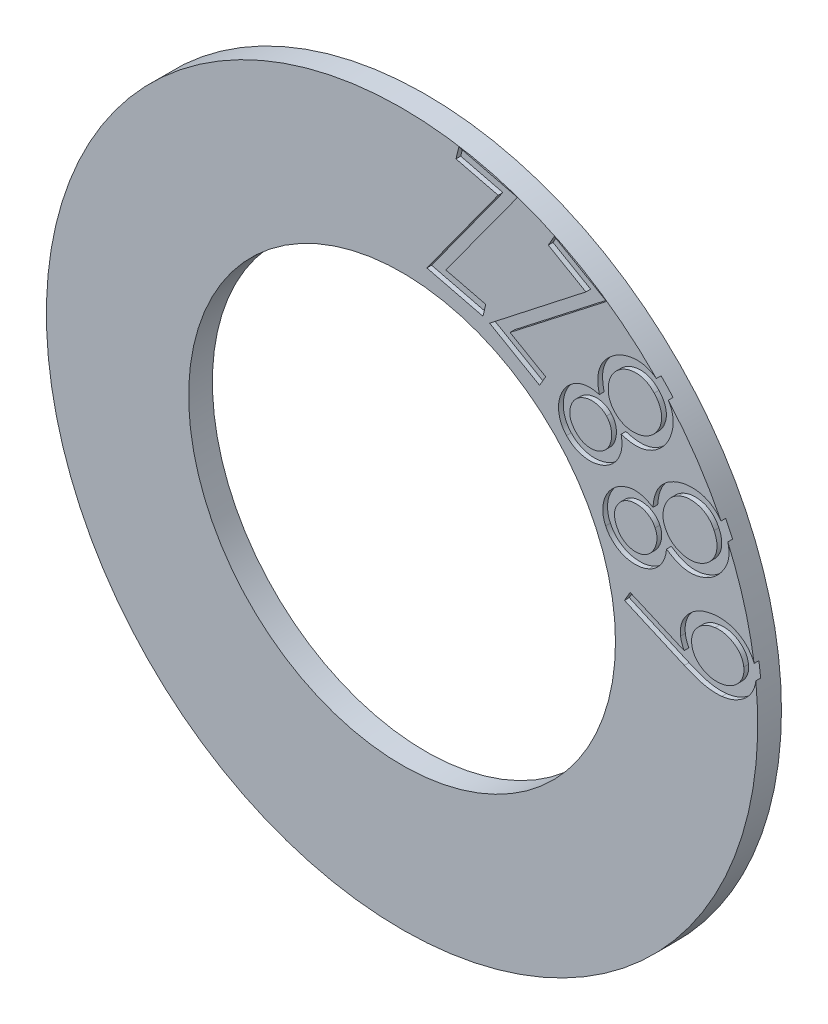
SolidWorks part; units mm, degrees
ref_plane "Ön Düzlem" through (0, 0, 0) normal (0, 0, 1) x (1, 0, 0)
ref_plane "Üst Düzlem" through (0, 0, 0) normal (0, 1, 0) x (1, 0, 0)
ref_plane "Sağ Düzlem" through (0, 0, 0) normal (1, 0, 0) x (0, 0, -1)
sketch "Çizim1" plane through (0, 0, 0) normal (0, 0, 1) x (1, 0, 0)
  circle A0 centre (0, 0) radius 4.5
  circle A1 centre (0, 0) radius 7.5
  dimension "D1" = 9
  dimension "D2" = 15
extrude "Yükseklik-Ekstrüzyon1" add sketch "Çizim1" along normal blind 0.5
sketch "Çizim3" plane through (0, 0, 0.5) normal (0, 0, 1) x (1, 0, 0)
  text T0 "688ZZ" font "Century Gothic" height in points 10
extrude "Kes-Ekstrüzyon1" cut sketch "Çizim3" against normal blind 0.1
